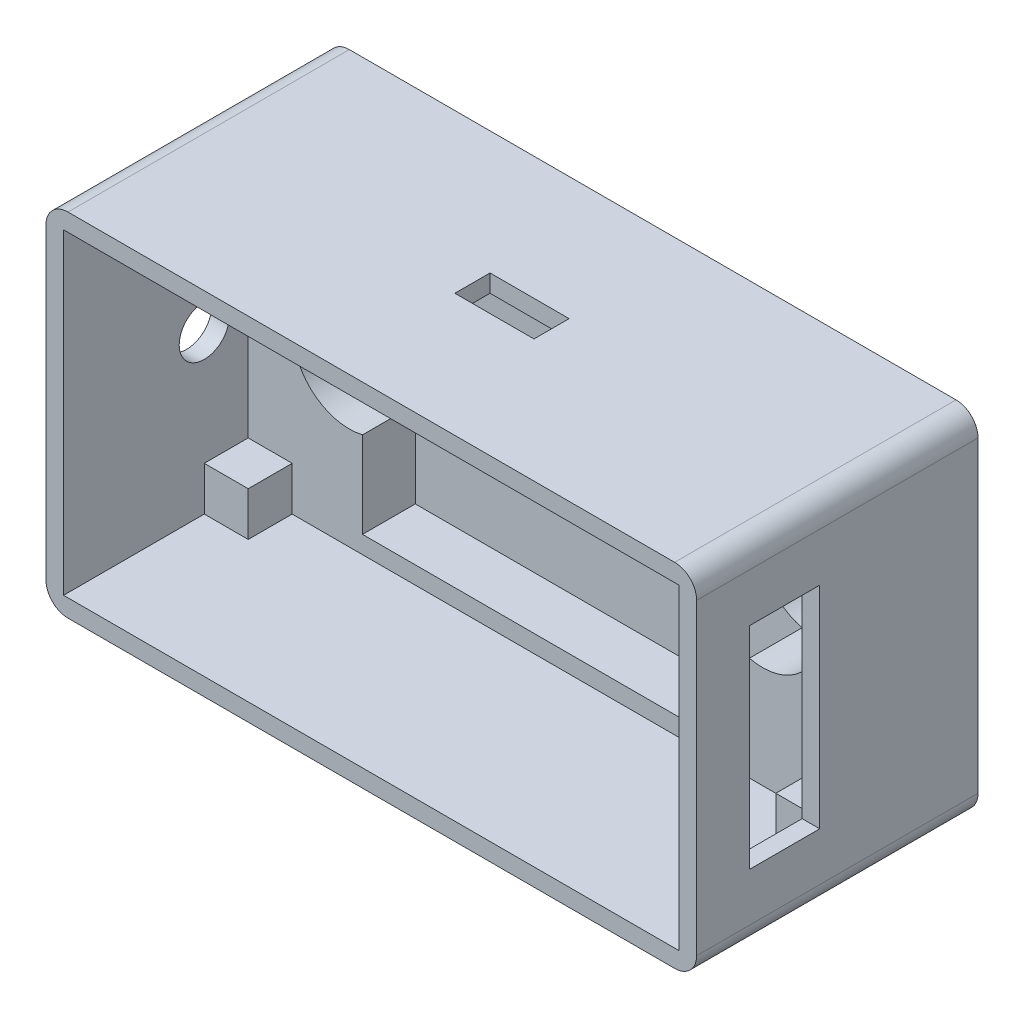
SolidWorks part; units mm, degrees
ref_plane "Front Plane" through (0, 0, 0) normal (0, 0, 1) x (1, 0, 0)
ref_plane "Top Plane" through (0, 0, 0) normal (0, 1, 0) x (1, 0, 0)
ref_plane "Right Plane" through (0, 0, 0) normal (1, 0, 0) x (0, 0, -1)
sketch "Sketch1" plane through (0, 0, 0) normal (0, 0, 1) x (1, 0, 0)
  line L1 (0, 0) -> (74, 0)
  line L2 (0, 0) -> (0, 40)
  line L3 (0, 40) -> (74, 40)
  line L4 (74, 0) -> (74, 40)
  dimension "D1" = 74
  dimension "D2" = 40
extrude "Boss-Extrude1" add sketch "Sketch1" along normal blind 32
sketch "Sketch2" plane through (0, 0, 32) normal (0, 0, 1) x (1, 0, 0)
  line L0 (74, 40) -> (0, 40) construction
  line L1 (2, 38) -> (72, 38)
  line L2 (2, 38) -> (2, 2)
  line L3 (2, 2) -> (72, 2)
  line L4 (72, 38) -> (72, 2)
  line L5 (0, 40) -> (0, 0) construction
  line L6 (74, 0) -> (74, 40) construction
  line L7 (0, 0) -> (74, 0) construction
  dimension "D1" = 2
  dimension "D2" = 2
  dimension "D3" = 2
  dimension "D4" = 2
extrude "Cut-Extrude1" cut sketch "Sketch2" against normal blind 21
sketch "Sketch3" plane through (0, 0, 11) normal (0, 0, 1) x (1, 0, 0)
  line L0 (2, 2) -> (72, 2) construction
  line L1 (15, 36) -> (59, 36)
  line L2 (15, 36) -> (15, 4)
  line L3 (15, 4) -> (59, 4)
  line L4 (59, 36) -> (59, 4)
  line L6 (72, 2) -> (72, 38) construction
  dimension "D1" = 32
  dimension "D2" = 44
  dimension "D3" = 2
  dimension "D4" = 13
extrude "Cut-Extrude2" cut sketch "Sketch3" against normal blind 6
sketch "Sketch4" plane through (0, 0, 5) normal (0, 0, 1) x (1, 0, 0)
  line L1 (72, 2) -> (72, 38) construction
  line L2 (2, 38) -> (2, 2) construction
  circle A1 centre (13.5, 20) radius 6.375
  circle A2 centre (60.5, 20) radius 6.375
  dimension "D1" = 11.5
  dimension "D2" = 12.75
  dimension "D3" = 12.75
  dimension "D4" = 11.5
extrude "Cut-Extrude3" cut sketch "Sketch4" along normal blind 35 and the other way blind 20
sketch "Sketch5" plane through (0, 0, 11) normal (0, 0, 1) x (1, 0, 0)
  line L0 (72, 2) -> (72, 38) construction
  line L1 (2, 38) -> (7, 38)
  line L2 (2, 38) -> (2, 33)
  line L3 (2, 33) -> (7, 33)
  line L4 (7, 38) -> (7, 33)
  line L5 (72, 38.6232) -> (67, 38.6232)
  line L6 (72, 38.6232) -> (72, 33.6232)
  line L7 (72, 33.6232) -> (67, 33.6232)
  line L8 (67, 38.6232) -> (67, 33.6232)
  line L9 (72, 2) -> (72, 38) construction
  line L11 (72, 2) -> (67, 2)
  line L12 (72, 2) -> (72, 7)
  line L13 (72, 7) -> (67, 7)
  line L14 (67, 2) -> (67, 7)
  line L15 (2, 2) -> (7, 2)
  line L16 (2, 2) -> (2, 7)
  line L17 (2, 7) -> (7, 7)
  line L18 (7, 2) -> (7, 7)
  dimension "D1" = 5
  dimension "D2" = 5
  dimension "D3" = 5
  dimension "D4" = 5
  dimension "D5" = 5
  dimension "D6" = 5
  dimension "D7" = 5
  dimension "D8" = 5
extrude "Boss-Extrude2" add sketch "Sketch5" along normal blind 5
sketch "Sketch6" plane through (74, 0, 0) normal (1, 0, 0) x (0, 0, -1)
  line L0 (-32, 40) -> (0, 40) construction
  line L1 (-26, 32) -> (-18, 32)
  line L2 (-26, 32) -> (-26, 8)
  line L3 (-26, 8) -> (-18, 8)
  line L4 (-18, 32) -> (-18, 8)
  line L5 (-32, 0) -> (0, 0) construction
  line L6 (-32, 0) -> (-32, 40) construction
  dimension "D1" = 8
  dimension "D2" = 24
  dimension "D3" = 8
  dimension "D4" = 8
  dimension "D5" = 14
extrude "Cut-Extrude4" cut sketch "Sketch6" against normal blind 5
sketch "Sketch7" plane through (0, 0, 0) normal (-1, 0, 0) x (0, 0, 1)
  circle A0 centre (16, 20.0797) radius 2.85
  dimension "D1" = 5.7
extrude "Cut-Extrude5" cut sketch "Sketch7" against normal blind 5
sketch "Sketch8" plane through (0, 40, 0) normal (0, 1, 0) x (1, 0, 0)
  line L0 (74, -32) -> (74, 0) construction
  line L1 (32.5, -18) -> (41.5, -18)
  line L2 (32.5, -18) -> (32.5, -14)
  line L3 (32.5, -14) -> (41.5, -14)
  line L4 (41.5, -18) -> (41.5, -14)
  line L6 (74, 0) -> (0, 0) construction
  dimension "D1" = 4
  dimension "D2" = 9
  dimension "D3" = 32.5
  dimension "D4" = 14
extrude "Cut-Extrude6" cut sketch "Sketch8" against normal blind 5
fillet "Fillet1" radius 2.5 4 edges at (74, 0, 16) (74, 40, 16) (0, 40, 16) (0, 0, 16)
